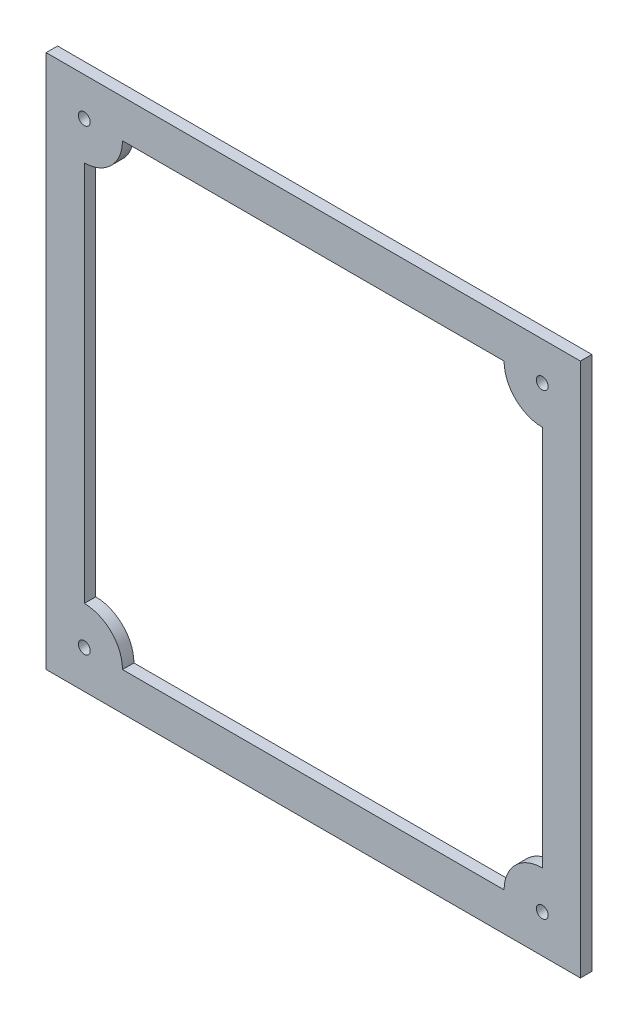
SolidWorks part; units mm, degrees
ref_plane "前基準面" through (0, 0, 0) normal (0, 0, 1) x (1, 0, 0)
ref_plane "上基準面" through (0, 0, 0) normal (0, 1, 0) x (1, 0, 0)
ref_plane "右基準面" through (0, 0, 0) normal (1, 0, 0) x (0, 0, -1)
sketch "草圖1" plane through (0, 0, 0) normal (0, 0, 1) x (1, 0, 0)
  line L1 (-70, -70) -> (70, -70)
  line L2 (-70, -70) -> (-70, 70)
  line L3 (-70, 70) -> (70, 70)
  line L4 (70, -70) -> (70, 70)
  line L5 (-70, -70) -> (70, 70) construction
  line L6 (-70, 70) -> (70, -70) construction
  line L7 (-60, -60) -> (60, -60) construction
  line L8 (-60, -60) -> (-60, 60) construction
  line L9 (-60, 60) -> (60, 60) construction
  line L10 (60, -60) -> (60, 60) construction
  line L11 (-60, -60) -> (60, 60) construction
  line L12 (-60, 60) -> (60, -60) construction
  circle A0 centre (-60, 60) radius 1.55
  circle A1 centre (60, 60) radius 1.55
  circle A2 centre (60, -60) radius 1.55
  circle A3 centre (-60, -60) radius 1.55
  point P0 (0, 0)
  point P6 (0, 0)
  dimension "D4" = 3.1
  dimension "D1" = 140
  dimension "D2" = 140
  dimension "D3" = 120
extrude "填料-伸長1" add sketch "草圖1" along normal blind 3
sketch "草圖2" plane through (0, 0, 3) normal (0, 0, 1) x (1, 0, 0)
  line L1 (-50, -60) -> (50, -60)
  line L2 (-60, -50) -> (-60, 50)
  line L3 (-50, 60) -> (50, 60)
  line L4 (60, -50) -> (60, 50)
  line L5 (-52.9289, -52.9289) -> (52.9289, 52.9289) construction
  line L6 (-52.9289, 52.9289) -> (52.9289, -52.9289) construction
  arc A0 (50, 60) -> (60, 50) centre (60, 60) ccw
  arc A1 (-60, 50) -> (-50, 60) centre (-60, 60) ccw
  arc A2 (-50, -60) -> (-60, -50) centre (-60, -60) ccw
  arc A3 (60, -50) -> (50, -60) centre (60, -60) ccw
  point P0 (0, 0)
  dimension "D1" = 20
extrude "除料-伸長1" cut sketch "草圖2" against normal through all
sketch "草圖3" plane through (0, 0, 3) normal (0, 0, 1) x (1, 0, 0)
  line L0 (-62.17, -57.83) -> (-62.17, -50)
  line L2 (-62.17, -57.83) -> (-62.17, -62.17)
  line L3 (-62.17, -62.17) -> (-57.83, -62.17)
  line L5 (-62.17, -57.83) -> (-57.83, -62.17) construction
  line L6 (-62.17, -62.17) -> (-57.83, -57.83) construction
  line L7 (-62.17, -50) -> (-70, -50)
  line L8 (-70, 70) -> (-70, -70) construction
  line L9 (-70, -50) -> (-70, -70)
  line L10 (-70, -70) -> (-50, -70)
  line L11 (-70, -70) -> (70, -70) construction
  line L12 (-50, -70) -> (-50, -62.17)
  line L13 (-50, -62.17) -> (-57.83, -62.17)
  point P0 (-60, -60)
  dimension "D1" = 4.34
  dimension "D2" = 4.34
